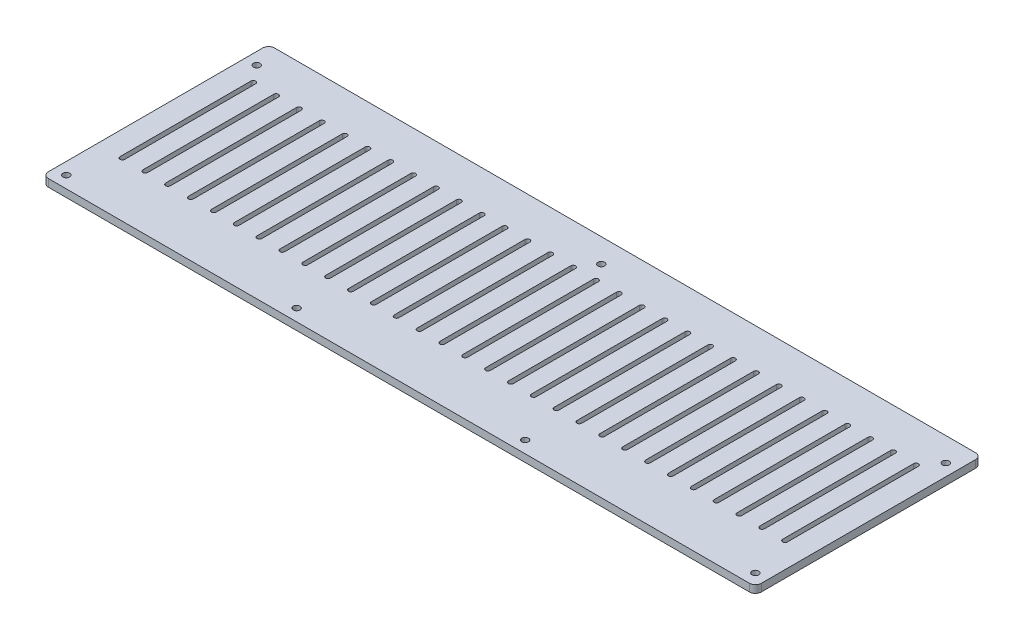
SolidWorks part; units mm, degrees
material "Acrylic (Medium-high impact)"
ref_plane "Front Plane" through (0, 0, 0) normal (0, 0, 1) x (1, 0, 0)
ref_plane "Top Plane" through (0, 0, 0) normal (0, 1, 0) x (1, 0, 0)
ref_plane "Right Plane" through (0, 0, 0) normal (1, 0, 0) x (0, 0, -1)
sketch "Sketch3" plane through (0, 0, 0) normal (0, 1, 0) x (1, 0, 0)
  line L0 (-71.45, 39.5) -> (-71.45, -47.5) construction
  line L1 (-139.75, 39.5) -> (-138.65, 39.5)
  line L2 (-139.75, 39.5) -> (-139.75, -47.5) construction
  line L3 (-139.75, -47.5) -> (-138.65, -47.5)
  line L4 (-138.65, 39.5) -> (-138.65, -47.5) construction
  line L5 (0, 47.5) -> (0, -47.5) construction
  line L6 (-129.05, 39.5) -> (-129.05, -47.5) construction
  line L7 (-130.15, 39.5) -> (-130.15, -47.5) construction
  line L8 (-130.15, -47.5) -> (-129.05, -47.5)
  line L9 (-130.15, 39.5) -> (-129.05, 39.5)
  line L10 (-119.45, 39.5) -> (-119.45, -47.5) construction
  line L11 (-120.55, 39.5) -> (-120.55, -47.5) construction
  line L12 (-120.55, -47.5) -> (-119.45, -47.5)
  line L13 (-120.55, 39.5) -> (-119.45, 39.5)
  line L14 (-109.85, 39.5) -> (-109.85, -47.5) construction
  line L15 (-110.95, 39.5) -> (-110.95, -47.5) construction
  line L16 (-110.95, -47.5) -> (-109.85, -47.5)
  line L17 (-110.95, 39.5) -> (-109.85, 39.5)
  line L18 (-100.25, 39.5) -> (-100.25, -47.5) construction
  line L19 (-101.35, 39.5) -> (-101.35, -47.5) construction
  line L20 (-101.35, -47.5) -> (-100.25, -47.5)
  line L21 (-101.35, 39.5) -> (-100.25, 39.5)
  line L22 (-90.65, 39.5) -> (-90.65, -47.5) construction
  line L23 (-91.75, 39.5) -> (-91.75, -47.5) construction
  line L24 (-91.75, -47.5) -> (-90.65, -47.5)
  line L25 (-91.75, 39.5) -> (-90.65, 39.5)
  line L26 (-81.05, 39.5) -> (-81.05, -47.5) construction
  line L27 (-82.15, 39.5) -> (-82.15, -47.5) construction
  line L28 (-82.15, -47.5) -> (-81.05, -47.5)
  line L29 (-82.15, 39.5) -> (-81.05, 39.5)
  line L30 (-72.55, 39.5) -> (-72.55, -47.5) construction
  line L31 (-72.55, -47.5) -> (-71.45, -47.5)
  line L32 (-72.55, 39.5) -> (-71.45, 39.5)
  line L33 (-61.85, 39.5) -> (-61.85, -47.5) construction
  line L34 (-62.95, 39.5) -> (-62.95, -47.5) construction
  line L35 (-62.95, -47.5) -> (-61.85, -47.5)
  line L36 (-62.95, 39.5) -> (-61.85, 39.5)
  line L37 (-52.25, 39.5) -> (-52.25, -47.5) construction
  line L38 (-53.35, 39.5) -> (-53.35, -47.5) construction
  line L39 (-53.35, -47.5) -> (-52.25, -47.5)
  line L40 (-53.35, 39.5) -> (-52.25, 39.5)
  line L41 (-42.65, 39.5) -> (-42.65, -47.5) construction
  line L42 (-43.75, 39.5) -> (-43.75, -47.5) construction
  line L43 (-43.75, -47.5) -> (-42.65, -47.5)
  line L44 (-147.25, 47.5) -> (147.25, 47.5)
  line L45 (-149.75, 45) -> (-149.75, -45)
  line L46 (-147.25, -47.5) -> (147.25, -47.5)
  line L47 (149.75, 45) -> (149.75, -45)
  line L48 (-43.75, 39.5) -> (-42.65, 39.5)
  line L49 (-33.05, 39.5) -> (-33.05, -47.5) construction
  line L50 (-34.15, 39.5) -> (-34.15, -47.5) construction
  line L51 (-34.15, -47.5) -> (-33.05, -47.5)
  line L52 (-34.15, 39.5) -> (-33.05, 39.5)
  line L53 (-23.45, 39.5) -> (-23.45, -47.5) construction
  line L54 (-24.55, 39.5) -> (-24.55, -47.5) construction
  line L55 (-24.55, -47.5) -> (-23.45, -47.5)
  line L56 (-24.55, 39.5) -> (-23.45, 39.5)
  line L57 (-13.85, 39.5) -> (-13.85, -47.5) construction
  line L58 (-14.95, 39.5) -> (-14.95, -47.5) construction
  line L59 (-14.95, -47.5) -> (-13.85, -47.5)
  line L60 (-14.95, 39.5) -> (-13.85, 39.5)
  line L61 (-4.25, 39.5) -> (-4.25, -47.5) construction
  line L62 (-5.35, 39.5) -> (-5.35, -47.5) construction
  line L63 (-5.35, -47.5) -> (-4.25, -47.5)
  line L64 (-5.35, 39.5) -> (-4.25, 39.5)
  line L65 (5.35, 39.5) -> (5.35, -47.5) construction
  line L66 (4.25, 39.5) -> (4.25, -47.5) construction
  line L67 (4.25, -47.5) -> (5.35, -47.5)
  line L68 (4.25, 39.5) -> (5.35, 39.5)
  line L69 (14.95, 39.5) -> (14.95, -47.5) construction
  line L70 (13.85, 39.5) -> (13.85, -47.5) construction
  line L71 (13.85, -47.5) -> (14.95, -47.5)
  line L72 (13.85, 39.5) -> (14.95, 39.5)
  line L73 (24.55, 39.5) -> (24.55, -47.5) construction
  line L74 (23.45, 39.5) -> (23.45, -47.5) construction
  line L75 (23.45, -47.5) -> (24.55, -47.5)
  line L76 (23.45, 39.5) -> (24.55, 39.5)
  line L77 (34.15, 39.5) -> (34.15, -47.5) construction
  line L78 (33.05, 39.5) -> (33.05, -47.5) construction
  line L79 (33.05, -47.5) -> (34.15, -47.5)
  line L80 (33.05, 39.5) -> (34.15, 39.5)
  line L81 (43.75, 39.5) -> (43.75, -47.5) construction
  line L82 (42.65, 39.5) -> (42.65, -47.5) construction
  line L83 (42.65, -47.5) -> (43.75, -47.5)
  line L84 (42.65, 39.5) -> (43.75, 39.5)
  line L85 (53.35, 39.5) -> (53.35, -47.5) construction
  line L86 (52.25, 39.5) -> (52.25, -47.5) construction
  line L87 (52.25, -47.5) -> (53.35, -47.5)
  line L88 (52.25, 39.5) -> (53.35, 39.5)
  line L89 (62.95, 39.5) -> (62.95, -47.5) construction
  line L90 (61.85, 39.5) -> (61.85, -47.5) construction
  line L91 (61.85, -47.5) -> (62.95, -47.5)
  line L92 (61.85, 39.5) -> (62.95, 39.5)
  line L93 (72.55, 39.5) -> (72.55, -47.5) construction
  line L94 (71.45, 39.5) -> (71.45, -47.5) construction
  line L95 (71.45, -47.5) -> (72.55, -47.5)
  line L96 (71.45, 39.5) -> (72.55, 39.5)
  line L97 (82.15, 39.5) -> (82.15, -47.5) construction
  line L98 (81.05, 39.5) -> (81.05, -47.5) construction
  line L99 (81.05, -47.5) -> (82.15, -47.5)
  line L100 (81.05, 39.5) -> (82.15, 39.5)
  line L101 (91.75, 39.5) -> (91.75, -47.5) construction
  line L102 (90.65, 39.5) -> (90.65, -47.5) construction
  line L103 (90.65, -47.5) -> (91.75, -47.5)
  line L104 (90.65, 39.5) -> (91.75, 39.5)
  line L105 (101.35, 39.5) -> (101.35, -47.5) construction
  line L106 (100.25, 39.5) -> (100.25, -47.5) construction
  line L107 (100.25, -47.5) -> (101.35, -47.5)
  line L108 (100.25, 39.5) -> (101.35, 39.5)
  line L109 (110.95, 39.5) -> (110.95, -47.5) construction
  line L110 (109.85, 39.5) -> (109.85, -47.5) construction
  line L111 (109.85, -47.5) -> (110.95, -47.5)
  line L112 (109.85, 39.5) -> (110.95, 39.5)
  line L113 (120.55, 39.5) -> (120.55, -47.5) construction
  line L114 (119.45, 39.5) -> (119.45, -47.5) construction
  line L115 (119.45, -47.5) -> (120.55, -47.5)
  line L116 (119.45, 39.5) -> (120.55, 39.5)
  line L117 (130.15, 39.5) -> (130.15, -47.5) construction
  line L118 (129.05, 39.5) -> (129.05, -47.5) construction
  line L119 (129.05, -47.5) -> (130.15, -47.5)
  line L120 (129.05, 39.5) -> (130.15, 39.5)
  line L121 (139.75, 39.5) -> (139.75, -47.5) construction
  line L122 (138.65, 39.5) -> (138.65, -47.5) construction
  line L123 (138.65, -47.5) -> (139.75, -47.5)
  line L124 (138.65, 39.5) -> (139.75, 39.5)
  line L125 (139.75, 39.5) -> (-139.75, 39.5) construction
  line L126 (-52.25, -42.5) -> (-43.75, -42.5) construction
  line L127 (43.75, -42.5) -> (52.25, -42.5) construction
  line L128 (-139.2, 30.5) -> (-139.2, -24.5) construction
  line L129 (-138.2, 30.5) -> (-138.2, -24.5)
  line L130 (-140.2, 30.5) -> (-140.2, -24.5)
  line L131 (-129.6, 30.5) -> (-129.6, -24.5) construction
  line L132 (-128.6, 30.5) -> (-128.6, -24.5)
  line L133 (-130.6, 30.5) -> (-130.6, -24.5)
  line L134 (-120, 30.5) -> (-120, -24.5) construction
  line L135 (-119, 30.5) -> (-119, -24.5)
  line L136 (-121, 30.5) -> (-121, -24.5)
  line L137 (-110.4, 30.5) -> (-110.4, -24.5) construction
  line L138 (-109.4, 30.5) -> (-109.4, -24.5)
  line L139 (-111.4, 30.5) -> (-111.4, -24.5)
  line L140 (-100.8, 30.5) -> (-100.8, -24.5) construction
  line L141 (-99.8, 30.5) -> (-99.8, -24.5)
  line L142 (-101.8, 30.5) -> (-101.8, -24.5)
  line L143 (-91.2, 30.5) -> (-91.2, -24.5) construction
  line L144 (-90.2, 30.5) -> (-90.2, -24.5)
  line L145 (-92.2, 30.5) -> (-92.2, -24.5)
  line L146 (-81.6, 30.5) -> (-81.6, -24.5) construction
  line L147 (-80.6, 30.5) -> (-80.6, -24.5)
  line L148 (-82.6, 30.5) -> (-82.6, -24.5)
  line L149 (-72, 30.5) -> (-72, -24.5) construction
  line L150 (-71, 30.5) -> (-71, -24.5)
  line L151 (-73, 30.5) -> (-73, -24.5)
  line L152 (-62.4, 30.5) -> (-62.4, -24.5) construction
  line L153 (-61.4, 30.5) -> (-61.4, -24.5)
  line L154 (-63.4, 30.5) -> (-63.4, -24.5)
  line L155 (-52.8, 30.5) -> (-52.8, -24.5) construction
  line L156 (-51.8, 30.5) -> (-51.8, -24.5)
  line L157 (-53.8, 30.5) -> (-53.8, -24.5)
  line L158 (-43.2, 30.5) -> (-43.2, -24.5) construction
  line L159 (-42.2, 30.5) -> (-42.2, -24.5)
  line L160 (-44.2, 30.5) -> (-44.2, -24.5)
  line L161 (-33.6, 30.5) -> (-33.6, -24.5) construction
  line L162 (-32.6, 30.5) -> (-32.6, -24.5)
  line L163 (-34.6, 30.5) -> (-34.6, -24.5)
  line L164 (-24, 30.5) -> (-24, -24.5) construction
  line L165 (-23, 30.5) -> (-23, -24.5)
  line L166 (-25, 30.5) -> (-25, -24.5)
  line L167 (-14.4, 30.5) -> (-14.4, -24.5) construction
  line L168 (-13.4, 30.5) -> (-13.4, -24.5)
  line L169 (-15.4, 30.5) -> (-15.4, -24.5)
  line L170 (-4.8, 30.5) -> (-4.8, -24.5) construction
  line L171 (-3.8, 30.5) -> (-3.8, -24.5)
  line L172 (-5.8, 30.5) -> (-5.8, -24.5)
  line L173 (4.8, 30.5) -> (4.8, -24.5) construction
  line L174 (5.8, 30.5) -> (5.8, -24.5)
  line L175 (3.8, 30.5) -> (3.8, -24.5)
  line L176 (14.4, 30.5) -> (14.4, -24.5) construction
  line L177 (15.4, 30.5) -> (15.4, -24.5)
  line L178 (13.4, 30.5) -> (13.4, -24.5)
  line L179 (24, 30.5) -> (24, -24.5) construction
  line L180 (25, 30.5) -> (25, -24.5)
  line L181 (23, 30.5) -> (23, -24.5)
  line L182 (33.6, 30.5) -> (33.6, -24.5) construction
  line L183 (34.6, 30.5) -> (34.6, -24.5)
  line L184 (32.6, 30.5) -> (32.6, -24.5)
  line L185 (43.2, 30.5) -> (43.2, -24.5) construction
  line L186 (44.2, 30.5) -> (44.2, -24.5)
  line L187 (42.2, 30.5) -> (42.2, -24.5)
  line L188 (52.8, 30.5) -> (52.8, -24.5) construction
  line L189 (53.8, 30.5) -> (53.8, -24.5)
  line L190 (51.8, 30.5) -> (51.8, -24.5)
  line L191 (62.4, 30.5) -> (62.4, -24.5) construction
  line L192 (63.4, 30.5) -> (63.4, -24.5)
  line L193 (61.4, 30.5) -> (61.4, -24.5)
  line L194 (72, 30.5) -> (72, -24.5) construction
  line L195 (73, 30.5) -> (73, -24.5)
  line L196 (71, 30.5) -> (71, -24.5)
  line L197 (81.6, 30.5) -> (81.6, -24.5) construction
  line L198 (82.6, 30.5) -> (82.6, -24.5)
  line L199 (80.6, 30.5) -> (80.6, -24.5)
  line L200 (91.2, 30.5) -> (91.2, -24.5) construction
  line L201 (92.2, 30.5) -> (92.2, -24.5)
  line L202 (90.2, 30.5) -> (90.2, -24.5)
  line L203 (100.8, 30.5) -> (100.8, -24.5) construction
  line L204 (101.8, 30.5) -> (101.8, -24.5)
  line L205 (99.8, 30.5) -> (99.8, -24.5)
  line L206 (110.4, 30.5) -> (110.4, -24.5) construction
  line L207 (111.4, 30.5) -> (111.4, -24.5)
  line L208 (109.4, 30.5) -> (109.4, -24.5)
  line L209 (120, 30.5) -> (120, -24.5) construction
  line L210 (121, 30.5) -> (121, -24.5)
  line L211 (119, 30.5) -> (119, -24.5)
  line L212 (129.6, 30.5) -> (129.6, -24.5) construction
  line L213 (130.6, 30.5) -> (130.6, -24.5)
  line L214 (128.6, 30.5) -> (128.6, -24.5)
  line L215 (139.2, 30.5) -> (139.2, -24.5) construction
  line L216 (140.2, 30.5) -> (140.2, -24.5)
  line L217 (138.2, 30.5) -> (138.2, -24.5)
  circle A0 centre (-144.75, 37.5) radius 1.4
  circle A1 centre (-144.75, -42.5) radius 1.4
  circle A2 centre (144.75, -42.5) radius 1.4
  circle A3 centre (144.75, 37.5) radius 1.4
  arc A4 (147.25, -47.5) -> (149.75, -45) centre (147.25, -45) ccw
  arc A5 (-149.75, -45) -> (-147.25, -47.5) centre (-147.25, -45) ccw
  arc A6 (147.25, 47.5) -> (149.75, 45) centre (147.25, 45) cw
  arc A7 (-147.25, 47.5) -> (-149.75, 45) centre (-147.25, 45) ccw
  circle A8 centre (-48, -42.5) radius 1.4
  circle A9 centre (48, -42.5) radius 1.4
  circle A10 centre (0, 37.5) radius 1.4
  arc A11 (-138.2, 30.5) -> (-140.2, 30.5) centre (-139.2, 30.5) ccw
  arc A12 (-140.2, -24.5) -> (-138.2, -24.5) centre (-139.2, -24.5) ccw
  arc A13 (-128.6, 30.5) -> (-130.6, 30.5) centre (-129.6, 30.5) ccw
  arc A14 (-130.6, -24.5) -> (-128.6, -24.5) centre (-129.6, -24.5) ccw
  arc A15 (-119, 30.5) -> (-121, 30.5) centre (-120, 30.5) ccw
  arc A16 (-121, -24.5) -> (-119, -24.5) centre (-120, -24.5) ccw
  arc A17 (-109.4, 30.5) -> (-111.4, 30.5) centre (-110.4, 30.5) ccw
  arc A18 (-111.4, -24.5) -> (-109.4, -24.5) centre (-110.4, -24.5) ccw
  arc A19 (-99.8, 30.5) -> (-101.8, 30.5) centre (-100.8, 30.5) ccw
  arc A20 (-101.8, -24.5) -> (-99.8, -24.5) centre (-100.8, -24.5) ccw
  arc A21 (-90.2, 30.5) -> (-92.2, 30.5) centre (-91.2, 30.5) ccw
  arc A22 (-92.2, -24.5) -> (-90.2, -24.5) centre (-91.2, -24.5) ccw
  arc A23 (-80.6, 30.5) -> (-82.6, 30.5) centre (-81.6, 30.5) ccw
  arc A24 (-82.6, -24.5) -> (-80.6, -24.5) centre (-81.6, -24.5) ccw
  arc A25 (-71, 30.5) -> (-73, 30.5) centre (-72, 30.5) ccw
  arc A26 (-73, -24.5) -> (-71, -24.5) centre (-72, -24.5) ccw
  arc A27 (-61.4, 30.5) -> (-63.4, 30.5) centre (-62.4, 30.5) ccw
  arc A28 (-63.4, -24.5) -> (-61.4, -24.5) centre (-62.4, -24.5) ccw
  arc A29 (-51.8, 30.5) -> (-53.8, 30.5) centre (-52.8, 30.5) ccw
  arc A30 (-53.8, -24.5) -> (-51.8, -24.5) centre (-52.8, -24.5) ccw
  arc A31 (-42.2, 30.5) -> (-44.2, 30.5) centre (-43.2, 30.5) ccw
  arc A32 (-44.2, -24.5) -> (-42.2, -24.5) centre (-43.2, -24.5) ccw
  arc A33 (-32.6, 30.5) -> (-34.6, 30.5) centre (-33.6, 30.5) ccw
  arc A34 (-34.6, -24.5) -> (-32.6, -24.5) centre (-33.6, -24.5) ccw
  arc A35 (-23, 30.5) -> (-25, 30.5) centre (-24, 30.5) ccw
  arc A36 (-25, -24.5) -> (-23, -24.5) centre (-24, -24.5) ccw
  arc A37 (-13.4, 30.5) -> (-15.4, 30.5) centre (-14.4, 30.5) ccw
  arc A38 (-15.4, -24.5) -> (-13.4, -24.5) centre (-14.4, -24.5) ccw
  arc A39 (-3.8, 30.5) -> (-5.8, 30.5) centre (-4.8, 30.5) ccw
  arc A40 (-5.8, -24.5) -> (-3.8, -24.5) centre (-4.8, -24.5) ccw
  arc A41 (5.8, 30.5) -> (3.8, 30.5) centre (4.8, 30.5) ccw
  arc A42 (3.8, -24.5) -> (5.8, -24.5) centre (4.8, -24.5) ccw
  arc A43 (15.4, 30.5) -> (13.4, 30.5) centre (14.4, 30.5) ccw
  arc A44 (13.4, -24.5) -> (15.4, -24.5) centre (14.4, -24.5) ccw
  arc A45 (25, 30.5) -> (23, 30.5) centre (24, 30.5) ccw
  arc A46 (23, -24.5) -> (25, -24.5) centre (24, -24.5) ccw
  arc A47 (34.6, 30.5) -> (32.6, 30.5) centre (33.6, 30.5) ccw
  arc A48 (32.6, -24.5) -> (34.6, -24.5) centre (33.6, -24.5) ccw
  arc A49 (44.2, 30.5) -> (42.2, 30.5) centre (43.2, 30.5) ccw
  arc A50 (42.2, -24.5) -> (44.2, -24.5) centre (43.2, -24.5) ccw
  arc A51 (53.8, 30.5) -> (51.8, 30.5) centre (52.8, 30.5) ccw
  arc A52 (51.8, -24.5) -> (53.8, -24.5) centre (52.8, -24.5) ccw
  arc A53 (63.4, 30.5) -> (61.4, 30.5) centre (62.4, 30.5) ccw
  arc A54 (61.4, -24.5) -> (63.4, -24.5) centre (62.4, -24.5) ccw
  arc A55 (73, 30.5) -> (71, 30.5) centre (72, 30.5) ccw
  arc A56 (71, -24.5) -> (73, -24.5) centre (72, -24.5) ccw
  arc A57 (82.6, 30.5) -> (80.6, 30.5) centre (81.6, 30.5) ccw
  arc A58 (80.6, -24.5) -> (82.6, -24.5) centre (81.6, -24.5) ccw
  arc A59 (92.2, 30.5) -> (90.2, 30.5) centre (91.2, 30.5) ccw
  arc A60 (90.2, -24.5) -> (92.2, -24.5) centre (91.2, -24.5) ccw
  arc A61 (101.8, 30.5) -> (99.8, 30.5) centre (100.8, 30.5) ccw
  arc A62 (99.8, -24.5) -> (101.8, -24.5) centre (100.8, -24.5) ccw
  arc A63 (111.4, 30.5) -> (109.4, 30.5) centre (110.4, 30.5) ccw
  arc A64 (109.4, -24.5) -> (111.4, -24.5) centre (110.4, -24.5) ccw
  arc A65 (121, 30.5) -> (119, 30.5) centre (120, 30.5) ccw
  arc A66 (119, -24.5) -> (121, -24.5) centre (120, -24.5) ccw
  arc A67 (130.6, 30.5) -> (128.6, 30.5) centre (129.6, 30.5) ccw
  arc A68 (128.6, -24.5) -> (130.6, -24.5) centre (129.6, -24.5) ccw
  arc A69 (140.2, 30.5) -> (138.2, 30.5) centre (139.2, 30.5) ccw
  arc A70 (138.2, -24.5) -> (140.2, -24.5) centre (139.2, -24.5) ccw
  point P33 (0, 39.5)
  point P156 (-139.2, 3)
  point P161 (-139.2, 39.5)
  point P162 (-139.2, 31.5)
  point P163 (139.2, 39.5)
  point P167 (-129.6, 3)
  point P172 (-129.6, 31.5)
  point P175 (-120, 3)
  point P180 (-120, 31.5)
  point P183 (-110.4, 3)
  point P188 (-110.4, 31.5)
  point P191 (-100.8, 3)
  point P196 (-100.8, 31.5)
  point P199 (-91.2, 3)
  point P204 (-91.2, 31.5)
  point P207 (-81.6, 3)
  point P212 (-81.6, 31.5)
  point P215 (-72, 3)
  point P220 (-72, 31.5)
  point P223 (-62.4, 3)
  point P228 (-62.4, 31.5)
  point P231 (-52.8, 3)
  point P236 (-52.8, 31.5)
  point P239 (-43.2, 3)
  point P244 (-43.2, 31.5)
  point P247 (-33.6, 3)
  point P252 (-33.6, 31.5)
  point P255 (-24, 3)
  point P260 (-24, 31.5)
  point P263 (-14.4, 3)
  point P268 (-14.4, 31.5)
  point P271 (-4.8, 3)
  point P276 (-4.8, 31.5)
  point P279 (4.8, 3)
  point P284 (4.8, 31.5)
  point P287 (14.4, 3)
  point P292 (14.4, 31.5)
  point P295 (24, 3)
  point P300 (24, 31.5)
  point P303 (33.6, 3)
  point P308 (33.6, 31.5)
  point P311 (43.2, 3)
  point P316 (43.2, 31.5)
  point P319 (52.8, 3)
  point P324 (52.8, 31.5)
  point P327 (62.4, 3)
  point P332 (62.4, 31.5)
  point P335 (72, 3)
  point P340 (72, 31.5)
  point P343 (81.6, 3)
  point P348 (81.6, 31.5)
  point P351 (91.2, 3)
  point P356 (91.2, 31.5)
  point P359 (100.8, 3)
  point P364 (100.8, 31.5)
  point P367 (110.4, 3)
  point P372 (110.4, 31.5)
  point P375 (120, 3)
  point P380 (120, 31.5)
  point P383 (129.6, 3)
  point P388 (129.6, 31.5)
  point P391 (139.2, 3)
  point P396 (139.2, 31.5)
  dimension "D7" = 10
  dimension "D8" = 5
  dimension "D9" = 85
  dimension "D10" = 5
  dimension "D6" = 2.8
  dimension "D11" = 2.5
  dimension "D12" = 5
  dimension "D15" = 1
  dimension "D2" = 1.1
  dimension "D3" = 8
  dimension "D5" = 8.5
  dimension "D13" = 8
  dimension "D14" = 55
  dimension "D16" = 30
  dimension "D4" = 30
extrude "Boss-Extrude1" add sketch "Sketch3" along normal blind 3.175 contours L44 A7 L45 A5 L46 L2 L1 L4 L7 L9 L6 L11 L13 L10 L15 L17 L14 L19 L21 L18 L23 L25 L22 L27 L29 L26 L30 L32 L0 L34 L36 L33 L38 L40 L37 L42 L48 L41 L50 L52
